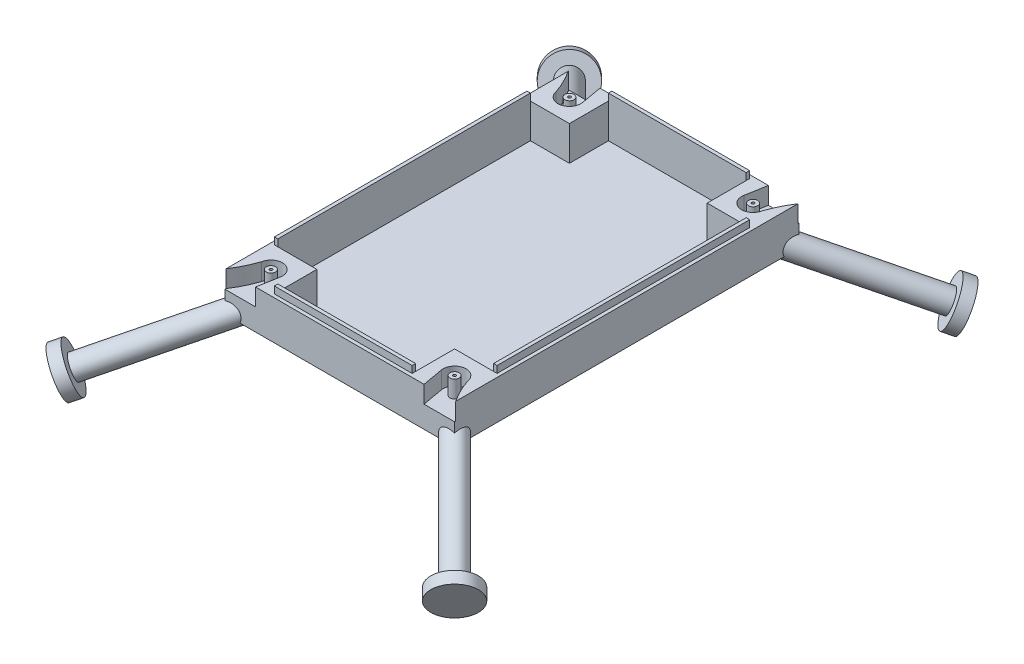
SolidWorks part; units mm, degrees
ref_plane "Alzado" through (0, 0, 0) normal (0, 0, 1) x (1, 0, 0)
ref_plane "Planta" through (0, 0, 0) normal (0, 1, 0) x (1, 0, 0)
ref_plane "Vista lateral" through (0, 0, 0) normal (1, 0, 0) x (0, 0, -1)
sketch "Croquis1" plane through (0, 0, 0) normal (0, 1, 0) x (1, 0, 0)
  line L1 (50, -75) -> (-50, -75)
  line L2 (50, -75) -> (50, 75)
  line L3 (50, 75) -> (-50, 75)
  line L4 (-50, -75) -> (-50, 75)
  line L5 (50, -75) -> (-50, 75) construction
  line L6 (50, 75) -> (-50, -75) construction
  point P0 (0, 0)
  dimension "D1" = 100
  dimension "D2" = 150
extrude "Saliente-Extruir1" add sketch "Croquis1" along normal blind 2
sketch "Croquis4" plane through (0, 2, 0) normal (0, 1, 0) x (1, 0, 0)
  line L0 (50, 75) -> (-50, 75) construction
  line L1 (0, 9.2093) -> (0, -8.4392) construction
  line L2 (-10.6413, 0) -> (10.8084, 0) construction
  line L3 (-50, 75) -> (-50, -75) construction
  line L4 (-40, 65) -> (-41.7365, 74.8481) construction
  line L9 (-44.924, 64.1318) -> (-46.6605, 73.9798)
  line L10 (-35.076, 65.8682) -> (-36.8124, 75.7163)
  line L11 (-40, 65) -> (-40, 89.0142) construction
  line L16 (40, -65) -> (41.7365, -74.8481) construction
  line L17 (44.924, -64.1318) -> (46.6605, -73.9798)
  line L18 (35.076, -65.8682) -> (36.8124, -75.7163)
  line L23 (40, 65) -> (41.7365, 74.8481) construction
  line L24 (44.924, 64.1318) -> (46.6605, 73.9798)
  line L25 (35.076, 65.8682) -> (36.8124, 75.7163)
  line L26 (-40, -65) -> (-41.7365, -74.8481) construction
  line L27 (-44.924, -64.1318) -> (-46.6605, -73.9798)
  line L28 (-35.076, -65.8682) -> (-36.8124, -75.7163)
  arc A1 (-44.924, 64.1318) -> (-35.076, 65.8682) centre (-40, 65) ccw
  arc A2 (-36.8124, 75.7163) -> (-46.6605, 73.9798) centre (-41.7365, 74.8481) ccw
  circle A3 centre (-40, 65) radius 2
  circle A4 centre (40, -65) radius 2
  arc A5 (44.924, -64.1318) -> (35.076, -65.8682) centre (40, -65) ccw
  arc A6 (36.8124, -75.7163) -> (46.6605, -73.9798) centre (41.7365, -74.8481) ccw
  circle A7 centre (40, 65) radius 2
  arc A8 (44.924, 64.1318) -> (35.076, 65.8682) centre (40, 65) cw
  arc A9 (36.8124, 75.7163) -> (46.6605, 73.9798) centre (41.7365, 74.8481) cw
  circle A10 centre (-40, -65) radius 2
  arc A11 (-44.924, -64.1318) -> (-35.076, -65.8682) centre (-40, -65) cw
  arc A12 (-36.8124, -75.7163) -> (-46.6605, -73.9798) centre (-41.7365, -74.8481) cw
  point P8 (-40.8682, 69.924)
  point P33 (40.8682, -69.924)
  point P40 (0, 0)
  point P45 (40.8682, 69.924)
  point P53 (-40.8682, -69.924)
  dimension "D1" = 5
  dimension "D8" = 4
  dimension "D2" = 10
  dimension "D3" = 10
  dimension "D6" = 10
  dimension "D9" = 2
sketch "Croquis5" plane through (0, 2, 0) normal (0, 1, 0) x (1, 0, 0)
  line L0 (-50, 75) -> (50, 75)
  line L1 (50, 75) -> (50, -75)
  line L2 (50, -75) -> (-50, -75)
  line L3 (-50, -75) -> (-50, 75)
  line L4 (-47, 72) -> (47, 72)
  line L5 (47, 72) -> (47, -72)
  line L6 (47, -72) -> (-47, -72)
  line L7 (-47, -72) -> (-47, 72)
  dimension "D1" = 3
  dimension "D2" = 3
  dimension "D3" = 3
  dimension "D4" = 3
extrude "Saliente-Extruir3" add sketch "Croquis5" along normal blind 15
sketch "Croquis6" plane through (0, 0, 0) normal (0, -1, 0) x (1, 0, 0)
  line L0 (0, 15.0618) -> (0, -13.0917) construction
  line L1 (-50, 75) -> (-30, 75)
  line L2 (-50, 75) -> (-50, 55)
  line L3 (-50, 55) -> (-30, 55)
  line L4 (-30, 75) -> (-30, 55)
  line L5 (-11.13, 0) -> (11.6828, 0) construction
  line L6 (-50, -75) -> (-30, -75)
  line L7 (-50, -75) -> (-50, -55)
  line L8 (-50, -55) -> (-30, -55)
  line L9 (-30, -75) -> (-30, -55)
  line L10 (50, -75) -> (30, -75)
  line L11 (30, -75) -> (30, -55)
  line L12 (50, -75) -> (50, -55)
  line L13 (50, -55) -> (30, -55)
  line L14 (50, 75) -> (50, 55)
  line L15 (50, 75) -> (30, 75)
  line L16 (30, 75) -> (30, 55)
  line L17 (50, 55) -> (30, 55)
  dimension "D1" = 20
  dimension "D2" = 20
extrude "Saliente-Extruir4" add sketch "Croquis6" against normal blind 17
extrude "Cortar-Extruir2" cut sketch "Croquis4" along normal through all
sketch "Croquis7" plane through (0, 2, 0) normal (0, 1, 0) x (1, 0, 0)
  line L0 (40, 65) -> (44.1111, 88.3154) construction
  line L1 (35.076, 65.8682) -> (39.1871, 89.1836)
  line L2 (44.924, 64.1318) -> (49.0352, 87.4471)
  line L3 (36.6861, 75) -> (35.076, 65.8682) construction
  line L4 (-40, 65) -> (-45.5922, 96.7151) construction
  line L5 (-44.924, 64.1318) -> (-50.5163, 95.8469)
  line L6 (-35.076, 65.8682) -> (-40.6682, 97.5834)
  line L7 (-46.6605, 73.9798) -> (-44.924, 64.1318) construction
  line L8 (-40, -65) -> (-41.7365, -74.8481) construction
  line L9 (-35.076, -65.8682) -> (-36.8124, -75.7163)
  line L10 (-44.924, -64.1318) -> (-46.6605, -73.9798)
  line L11 (-44.924, -64.1318) -> (-46.6605, -73.9798) construction
  line L12 (40, -65) -> (42.6116, -79.8112) construction
  line L13 (44.924, -64.1318) -> (47.5357, -78.943)
  line L14 (35.076, -65.8682) -> (37.6876, -80.6795)
  line L15 (35.076, -65.8682) -> (36.6861, -75) construction
  arc A0 (35.076, 65.8682) -> (44.924, 64.1318) centre (40, 65) ccw
  arc A1 (49.0352, 87.4471) -> (39.1871, 89.1836) centre (44.1111, 88.3154) ccw
  arc A2 (-44.924, 64.1318) -> (-35.076, 65.8682) centre (-40, 65) ccw
  arc A3 (-40.6682, 97.5834) -> (-50.5163, 95.8469) centre (-45.5922, 96.7151) ccw
  arc A4 (-35.076, -65.8682) -> (-44.924, -64.1318) centre (-40, -65) ccw
  arc A5 (-46.6605, -73.9798) -> (-36.8124, -75.7163) centre (-41.7365, -74.8481) ccw
  arc A6 (44.924, -64.1318) -> (35.076, -65.8682) centre (40, -65) ccw
  arc A7 (37.6876, -80.6795) -> (47.5357, -78.943) centre (42.6116, -79.8112) ccw
  point P3 (42.0556, 76.6577)
  point P13 (-42.7961, 80.8576)
  point P23 (-40.8682, -69.924)
  point P33 (41.3058, -72.4056)
  dimension "D1" = 10
extrude "Saliente-Extruir5" add sketch "Croquis7" along normal blind 7.5
sketch "Croquis8" plane through (0, 0, 0) normal (0, -1, 0) x (1, 0, 0)
  line L1 (50, -75) -> (-50, -75)
  line L2 (50, -75) -> (50, 75)
  line L3 (50, 75) -> (-50, 75)
  line L4 (-50, -75) -> (-50, 75)
  line L5 (50, -75) -> (-50, 75) construction
  line L6 (50, 75) -> (-50, -75) construction
  line L7 (63.9694, -105.7943) -> (-63.9694, -105.7943)
  line L8 (63.9694, -105.7943) -> (63.9694, 105.7943)
  line L9 (63.9694, 105.7943) -> (-63.9694, 105.7943)
  line L10 (-63.9694, -105.7943) -> (-63.9694, 105.7943)
  line L11 (63.9694, -105.7943) -> (-63.9694, 105.7943) construction
  line L12 (63.9694, 105.7943) -> (-63.9694, -105.7943) construction
  point P0 (0, 0)
  point P7 (0, 0)
extrude "Cortar-Extruir3" cut sketch "Croquis8" against normal through all
sketch "Croquis9" plane through (0, 17, 0) normal (0, 1, 0) x (1, 0, 0)
  line L0 (-50, 75) -> (-50, -75) construction
  line L1 (-50, -74.5) -> (-50, -75)
  line L2 (-50, -75) -> (-44.5116, -75)
  line L3 (-44.5116, -75) -> (-44.5116, -62.8446)
  line L4 (50, -75) -> (44.5116, -75)
  line L5 (50, -74.5) -> (50, -75)
  line L6 (44.5116, -75) -> (44.5116, -62.8446)
  line L7 (-46.7342, -75) -> (-36.6861, -75) construction
  line L8 (0, 24.5464) -> (0, -20.77) construction
  line L9 (-13.0871, 0) -> (31.2548, 0) construction
  line L10 (-50, 75) -> (-44.5116, 75)
  line L11 (-50, 74.5) -> (-50, 75)
  line L12 (-44.5116, 75) -> (-44.5116, 62.8446)
  line L13 (50, 75) -> (44.5116, 75)
  line L14 (50, 74.5) -> (50, 75)
  line L15 (44.5116, 75) -> (44.5116, 62.8446)
  arc A0 (-35.076, -65.8682) -> (-44.924, -64.1318) centre (-40, -65) ccw construction
  spline S0 degree 2 poles (-50, -74.5) (-46.3883, -69.0215) (-44.5116, -62.8446) knots 0 0 0 1 1 1
  spline S1 degree 2 poles (50, -74.5) (46.3883, -69.0215) (44.5116, -62.8446) knots 0 0 0 1 1 1
  spline S2 degree 2 poles (-50, 74.5) (-46.3883, 69.0215) (-44.5116, 62.8446) knots 0 0 0 1 1 1
  spline S3 degree 2 poles (50, 74.5) (46.3883, 69.0215) (44.5116, 62.8446) knots 0 0 0 1 1 1
  dimension "D1" = 0.5
extrude "Cortar-Extruir4" cut sketch "Croquis9" against normal blind 7.5
sketch "Croquis10" plane through (0, 17, 0) normal (0, 1, 0) x (1, 0, 0)
  line L0 (-30, 72) -> (-30, 73.5)
  line L1 (-30, 73.5) -> (30, 73.5)
  line L2 (30, 73.5) -> (30, 72)
  line L4 (-30, 72) -> (30, 72)
  line L5 (-18.7367, 0) -> (31.7081, 0) construction
  line L6 (30, -73.5) -> (30, -72)
  line L7 (-30, -72) -> (-30, -73.5)
  line L8 (-30, -73.5) -> (30, -73.5)
  line L9 (-30, -72) -> (30, -72)
  line L10 (-47, 55) -> (-30, 55) construction
  line L11 (-47, -55) -> (-48.5, -55)
  line L12 (-47, -55) -> (-47, 55)
  line L13 (-47, 55) -> (-48.5, 55)
  line L14 (-48.5, -55) -> (-48.5, 55)
  line L15 (0, 12.8361) -> (0, -10.3832) construction
  line L16 (47, -55) -> (48.5, -55)
  line L17 (47, 55) -> (48.5, 55)
  line L18 (48.5, -55) -> (48.5, 55)
  line L19 (47, -55) -> (47, 55)
  dimension "D1" = 1.5
  dimension "D2" = 1.5
extrude "Saliente-Extruir6" add sketch "Croquis10" along normal blind 3
sketch "Croquis11" plane through (0, 0, 0) normal (0, 1, 0) x (1, 0, 0)
  line L0 (-40, 65) -> (-41.7365, 74.8481) construction
  line L1 (-44.924, 64.1318) -> (-46.6605, 73.9798)
  line L2 (-35.076, 65.8682) -> (-36.8124, 75.7163)
  line L3 (-35.076, 65.8682) -> (-36.6861, 75) construction
  line L4 (-41.7365, 74.8481) -> (-94.1622, 111.557) construction
  line L5 (-44.6044, 70.7523) -> (-97.0301, 107.4612) construction
  line L6 (-38.8686, 78.9438) -> (-91.2943, 115.6527) construction
  circle A0 centre (0, 0) radius 165 construction
  arc A1 (-44.924, 64.1318) -> (-35.076, 65.8682) centre (-40, 65) ccw
  arc A2 (-36.8124, 75.7163) -> (-46.6605, 73.9798) centre (-41.7365, 74.8481) ccw
  circle A3 centre (-41.7365, 74.8481) radius 5 construction
  arc A4 (-44.6044, 70.7523) -> (-38.8686, 78.9438) centre (-41.7365, 74.8481) ccw construction
  arc A5 (-91.2943, 115.6527) -> (-97.0301, 107.4612) centre (-94.1622, 111.557) ccw construction
  point P6 (-40.8682, 69.924)
  point P15 (-67.9493, 93.2025)
  dimension "D1" = 330
  dimension "D4" = 5
  dimension "D2" = 10
  dimension "D3" = 64
  dimension "D5" = 135
sketch "Croquis12" plane through (0, 17, 0) normal (0, 1, 0) x (1, 0, 0)
  line L0 (0, 13.4006) -> (0, -9.9782) construction
  line L1 (-10.6808, 0) -> (14.9677, 0) construction
  circle A0 centre (-40, -65) radius 0.6
  circle A1 centre (-40, 65) radius 0.6
  circle A2 centre (40, 65) radius 0.6
  circle A3 centre (40, -65) radius 0.6
  dimension "D1" = 1.2
extrude "Cortar-Extruir5" cut sketch "Croquis12" against normal blind 2
ref_plane "Plano3" through (-12.5, 0, -12.5) normal (-0.7071, 0, -0.7071) x (-0.7071, 0, 0.7071)
sketch "Croquis17" plane through (-12.5, 0, -12.5) normal (-0.7071, 0, -0.7071) x (-0.7071, 0, 0.7071)
  line L0 (-74.3883, 5.813) -> (-139.6445, -21.8602)
  line L2 (-139.6445, -21.8602) -> (-143.5181, -12.7259)
  line L4 (-143.5181, -12.7259) -> (-138.9149, -10.7738)
  line L5 (-138.9149, -10.7738) -> (-136.9628, -15.377)
  line L6 (-136.9628, -15.377) -> (-77.1213, 10)
  line L9 (-77.1213, 10) -> (-74.3883, 5.813)
  line L10 (165, 0) -> (-165, 0) construction
  line L11 (-88.3883, 9.5) -> (-88.3883, 0) construction
  dimension "D1" = 5
  dimension "D2" = 10
  dimension "D4" = 5
  dimension "D6" = 14
revolve "Revolución4" add sketch "Croquis17" angle 360 about L0
mirror "Simetría4" about plane through (0, 0, 0) normal (0, 0, 1) of "Revolución4"
mirror "Simetría5" about plane through (0, 0, 0) normal (1, 0, 0) of "Simetría4", "Revolución4"
sketch "Croquis19" plane through (0, 9.5, 0) normal (0, 1, 0) x (1, 0, 0)
  line L0 (-43.417, -64.899) -> (-39.6924, -68.2642)
  line L1 (-43.417, -64.899) -> (-45.7191, -67.447)
  line L2 (-39.6924, -68.2642) -> (-41.9946, -70.8122)
  line L3 (-45.7191, -67.447) -> (-41.9946, -70.8122)
  line L4 (-10.2444, 0) -> (21.0475, 0) construction
  line L5 (0, 18.513) -> (0, -18.4289) construction
  line L6 (39.6924, -68.2642) -> (41.9946, -70.8122)
  line L7 (45.7191, -67.447) -> (41.9946, -70.8122)
  line L8 (43.417, -64.899) -> (45.7191, -67.447)
  line L9 (43.417, -64.899) -> (39.6924, -68.2642)
  line L10 (43.417, 64.899) -> (39.6924, 68.2642)
  line L11 (43.417, 64.899) -> (45.7191, 67.447)
  line L12 (45.7191, 67.447) -> (41.9946, 70.8122)
  line L13 (39.6924, 68.2642) -> (41.9946, 70.8122)
  line L14 (-39.6924, 68.2642) -> (-41.9946, 70.8122)
  line L15 (-45.7191, 67.447) -> (-41.9946, 70.8122)
  line L16 (-43.417, 64.899) -> (-45.7191, 67.447)
  line L17 (-43.417, 64.899) -> (-39.6924, 68.2642)
extrude "Cortar-Extruir7" cut sketch "Croquis19" along normal through all
